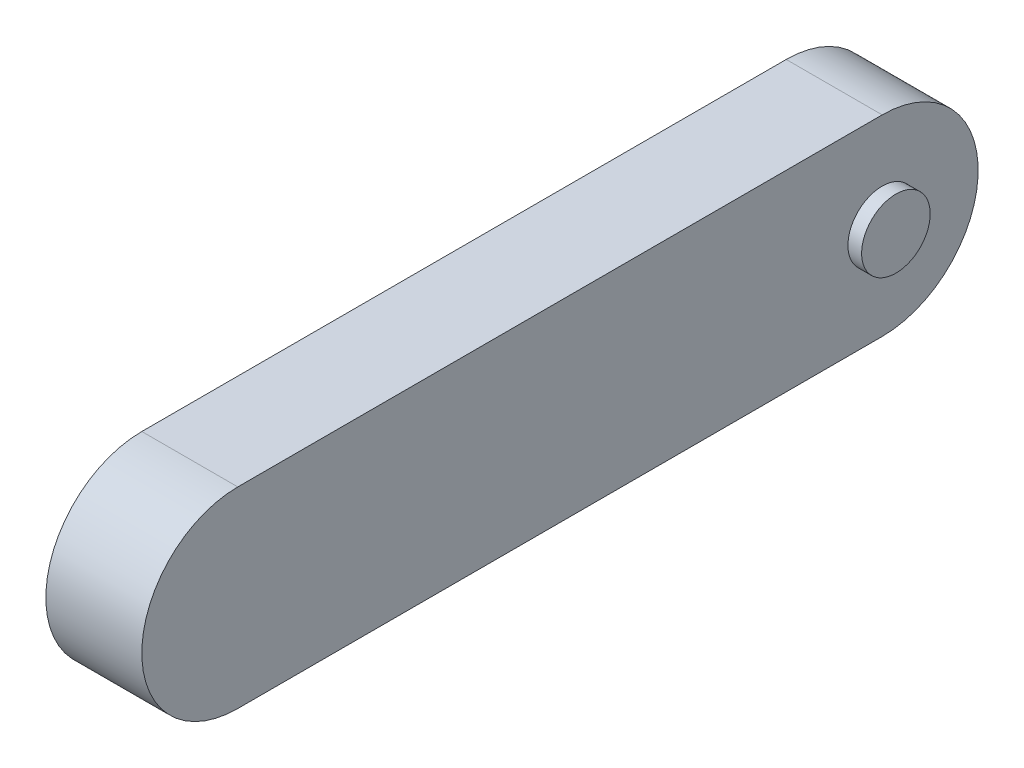
SolidWorks part; units mm, degrees
ref_plane "Front Plane" through (0, 0, 0) normal (0, 0, 1) x (1, 0, 0)
ref_plane "Top Plane" through (0, 0, 0) normal (0, 1, 0) x (1, 0, 0)
ref_plane "Right Plane" through (0, 0, 0) normal (1, 0, 0) x (0, 0, -1)
sketch "Sketch3" plane through (0, 0, 0) normal (1, 0, 0) x (0, 0, -1)
  circle A0 centre (0, 0) radius 70
  dimension "D1" = 140
extrude "Boss-Extrude1" add sketch "Sketch3" along normal blind 70
sketch "Sketch4" plane through (0, 0, 0) normal (1, 0, 0) x (0, 0, -1)
  circle A0 centre (0, 0) radius 25
  dimension "D1" = 50
extrude "Boss-Extrude2" add sketch "Sketch4" against normal blind 10
ref_plane "Plane1" through (70, 0, 0) normal (1, 0, 0) x (0, 0, -1)
sketch "Sketch6" plane through (70, 0, 0) normal (1, 0, 0) x (0, 0, -1)
  circle A0 centre (0, 0) radius 25
  dimension "D1" = 50
extrude "Boss-Extrude3" add sketch "Sketch6" along normal blind 10 contours A0
ref_plane "Plane2" through (0, 70, 0) normal (0, 1, 0) x (1, 0, 0)
sketch "Sketch7" plane through (0, 70, 0) normal (0, 1, 0) x (1, 0, 0)
  line L0 (70, -70) -> (70, -470)
  line L1 (70, -70) -> (0, -70)
  line L2 (0, -70) -> (0, -470)
  line L3 (0, -470) -> (70, -470)
  dimension "D1" = 400
extrude "Boss-Extrude4" add sketch "Sketch7" against normal blind 140 separate body contours L3 L0 L1 L2
ref_plane "Plane3" through (70, 0, 0) normal (1, 0, 0) x (0, 0, -1)
sketch "Sketch8" plane through (70, 0, 0) normal (1, 0, 0) x (0, 0, -1)
  line L0 (0, 70) -> (-70, 70)
  line L1 (-70, 70) -> (-70, -70)
  line L2 (-70, -70) -> (0, -70)
  circle A0 centre (0, 0) radius 70 construction
  arc A1 (0, 70) -> (0, -70) centre (0, 0) ccw
extrude "Boss-Extrude5" add sketch "Sketch8" against normal blind 70 contours A1 L0 L1 | A1 L1 L2
ref_plane "Plane5" through (0, 0, 0) normal (1, 0, 0) x (0, 0, -1)
sketch "Sketch9" plane through (0, 0, 0) normal (1, 0, 0) x (0, 0, -1)
  line L0 (-470, -70) -> (-470, 70) construction
  line L1 (-470, 70) -> (-470, -70)
  arc A0 (-470, 70) -> (-470, -70) centre (-470, 0) ccw
  dimension "D1" = 140
extrude "Boss-Extrude6" add sketch "Sketch9" along normal blind 70
